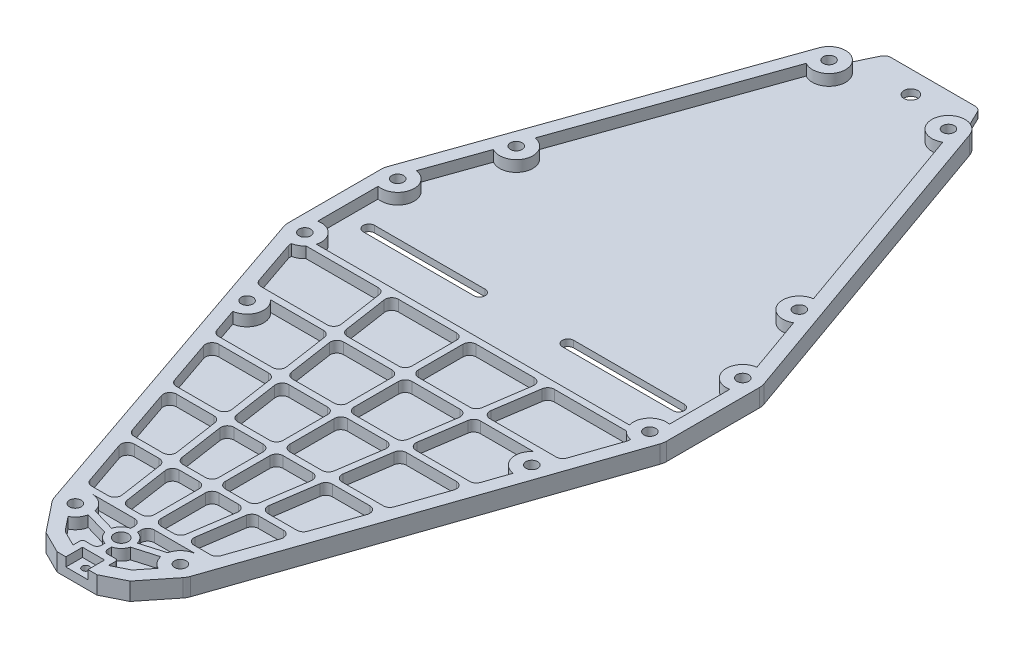
SolidWorks part; units mm, degrees
material "6061-T6 (SS)"
ref_plane "Front Plane" through (0, 0, 0) normal (0, 0, 1) x (1, 0, 0)
ref_plane "Top Plane" through (0, 0, 0) normal (0, 1, 0) x (1, 0, 0)
ref_plane "Right Plane" through (0, 0, 0) normal (1, 0, 0) x (0, 0, -1)
sketch "Sketch1" plane through (0, 0, 0) normal (0, 1, 0) x (1, 0, 0)
  line L0 (0, 0) -> (0, 185) construction
  line L1 (0, 0) -> (0, -202)
  line L2 (19.1123, 185) -> (-19.1123, 185)
  line L3 (-21.8169, 183.2982) -> (-27, 172.5)
  line L4 (-27, 165) -> (-78, 21) construction
  line L5 (-78, 21) -> (-78, -21) construction
  line L6 (-78, -21) -> (-23.75, -179) construction
  line L7 (-34.0697, 167.5039) -> (-85.5, 22.2889)
  line L8 (-85.5, 0) -> (-85.5, 22.2889)
  line L12 (-85.5, -21) -> (-85.5, 21)
  line L13 (-85.5, 0) -> (-85.5, -22.2517)
  line L14 (-30.8435, -181.4356) -> (-85.5, -22.2517)
  line L15 (9, -202) -> (-9, -202)
  line L16 (-9, -202) -> (-19, -197)
  line L17 (-19, -197) -> (-29.6428, -183.6395)
  line L18 (78, -21) -> (23.75, -179) construction
  line L19 (78, 21) -> (78, -21) construction
  line L20 (27, 165) -> (78, 21) construction
  line L21 (19, -197) -> (29.6428, -183.6395)
  line L22 (9, -202) -> (19, -197)
  line L23 (30.8435, -181.4356) -> (85.5, -22.2517)
  line L24 (85.5, 0) -> (85.5, -22.2517)
  line L25 (85.5, -21) -> (85.5, 21)
  line L29 (85.5, 0) -> (85.5, 22.2889)
  line L30 (34.0697, 167.5039) -> (85.5, 22.2889)
  line L31 (21.8169, 183.2982) -> (27, 172.5)
  line L32 (85.5, 0) -> (-85.5, 0) construction
  line L35 (-20, 0) -> (-70, 0) construction
  line L36 (-20, -2.55) -> (-70, -2.55)
  line L37 (-20, 2.55) -> (-70, 2.55)
  line L38 (20, 0) -> (70, 0) construction
  line L39 (20, -2.55) -> (70, -2.55)
  line L40 (20, 2.55) -> (70, 2.55)
  circle A0 centre (0, 0) radius 4.5
  circle A1 centre (0, 175) radius 3.15
  circle A2 centre (-27, 165) radius 2.65
  circle A3 centre (-78, 21) radius 2.65
  circle A4 centre (-78, -21) radius 2.65
  circle A5 centre (-23.75, -179) radius 2.65
  circle A6 centre (0, -198) radius 1.65
  circle A7 centre (0, -182) radius 3.15
  circle A9 centre (-27, 165) radius 7.5
  circle A10 centre (-78, 21) radius 7.5
  circle A11 centre (-78, -21) radius 7.5
  circle A12 centre (-23.75, -179) radius 7.5
  circle A13 centre (-63.9784, 60.5903) radius 2.65
  circle A14 centre (-63.9784, 60.5903) radius 7.5
  circle A15 centre (-64.3607, -60.7237) radius 2.65
  circle A16 centre (-64.3607, -60.7237) radius 7.5
  circle A17 centre (64.3607, -60.7237) radius 7.5
  circle A18 centre (64.3607, -60.7237) radius 2.65
  circle A19 centre (63.9784, 60.5903) radius 7.5
  circle A20 centre (63.9784, 60.5903) radius 2.65
  circle A21 centre (23.75, -179) radius 7.5
  circle A22 centre (78, -21) radius 7.5
  circle A23 centre (78, 21) radius 7.5
  circle A24 centre (27, 165) radius 7.5
  circle A25 centre (23.75, -179) radius 2.65
  circle A26 centre (78, -21) radius 2.65
  circle A27 centre (78, 21) radius 2.65
  circle A28 centre (27, 165) radius 2.65
  arc A31 (-20, -2.55) -> (-20, 2.55) centre (-20, 0) ccw
  arc A32 (-70, 2.55) -> (-70, -2.55) centre (-70, 0) ccw
  arc A33 (20, -2.55) -> (20, 2.55) centre (20, 0) cw
  arc A34 (70, 2.55) -> (70, -2.55) centre (70, 0) cw
  arc A35 (21.8169, 183.2982) -> (19.1123, 185) centre (19.1123, 182) ccw
  arc A36 (-19.1123, 185) -> (-21.8169, 183.2982) centre (-19.1123, 182) ccw
  point P73 (-45, 0)
  point P80 (45, 0)
  point P87 (21, 185)
  point P90 (-21, 185)
  dimension "D14" = 3.3
  dimension "D15" = 6.3
  dimension "D16" = 5.3
  dimension "D17" = 5.3
  dimension "D18" = 9
  dimension "D19" = 5.3
  dimension "D20" = 5.3
  dimension "D21" = 6.3
  dimension "D24" = 15
  dimension "D23" = 15
  dimension "D25" = 15
  dimension "D26" = 15
  dimension "D27" = 5.3
  dimension "D28" = 15
  dimension "D31" = 5.3
  dimension "D32" = 15
  dimension "D45" = 70
  dimension "D43" = 2.55
  dimension "D47" = 3
  dimension "D1" = 21
  dimension "D2" = 21
  dimension "D3" = 165
  dimension "D4" = 182
  dimension "79" = 179
  dimension "D5" = 175
  dimension "D6" = 198
  dimension "D7" = 185
  dimension "D8" = 202
  dimension "D9" = 27
  dimension "D10" = 78
  dimension "D11" = 78
  dimension "D12" = 23.75
  dimension "D13" = 0
  dimension "D22" = 21
  dimension "D29" = 42
  dimension "D30" = 42
  dimension "D33" = 7.5
  dimension "D34" = 7.5
  dimension "D35" = 7.5
  dimension "D36" = 22.2889
  dimension "D37" = 7.5
  dimension "D38" = 7.5
  dimension "D39" = 10
  dimension "D40" = 5
  dimension "D41" = 9
  dimension "D42" = 13.3605
  dimension "D44" = 50
  dimension "D46" = 7.5
extrude "Boss-Extrude2" add sketch "Sketch1" along normal blind 8
sketch "Sketch2" plane through (0, 8, 0) normal (0, 1, 0) x (1, 0, 0)
  line L0 (0, -202) -> (0, 185) construction
  line L1 (9, -202) -> (-9, -202) construction
  line L2 (19.1123, 185) -> (-19.1123, 185) construction
  line L3 (-30.8672, 158.5739) -> (-76.9607, 28.4276)
  line L4 (-34.0697, 167.5039) -> (-85.0697, 23.5039) construction
  line L5 (-79.5, 13.6515) -> (-79.5, -13.6515)
  line L6 (-85.5, -21) -> (-85.5, 21) construction
  line L7 (-29.6367, -166.4742) -> (-77.0323, -28.4373)
  line L8 (-30.8435, -181.4356) -> (-85.0935, -23.4356) construction
  line L9 (-20.3446, -185.6823) -> (-15.5447, -191.7078)
  line L10 (-14.5399, -192.5219) -> (-8.217, -195.6833)
  line L11 (-6.8754, -196) -> (6.8754, -196)
  line L12 (-19, -197) -> (-29.6428, -183.6395) construction
  line L13 (-9, -202) -> (-19, -197) construction
  line L14 (-8, -202) -> (-8, -192.5)
  line L15 (-7, -191.5) -> (-3.5, -191.5)
  line L16 (0, -168.5) -> (-28.9412, -168.5) construction
  line L17 (-1.5, -23) -> (-70.7716, -23)
  line L18 (-1.5, -29) -> (-1.5, -49.1)
  line L19 (-4.5, -52.1) -> (-27.6998, -52.1)
  line L20 (-30.6671, -49.5418) -> (-33.6601, -29.4418)
  line L21 (-30.6928, -26) -> (-4.5, -26)
  line L22 (-1.5, -58.1) -> (-1.5, -78.2)
  line L23 (-4.5, -81.2) -> (-23.3668, -81.2)
  line L24 (-26.3341, -78.6418) -> (-29.327, -58.5418)
  line L25 (-26.3597, -55.1) -> (-4.5, -55.1)
  line L26 (-1.5, -87.2) -> (-1.5, -107.3)
  line L27 (-4.5, -110.3) -> (-19.0338, -110.3)
  line L28 (-22.001, -107.7418) -> (-24.994, -87.6418)
  line L29 (-22.0267, -84.2) -> (-4.5, -84.2)
  line L30 (-1.5, -145.4) -> (-1.5, -165.5)
  line L31 (-4.5, -168.5) -> (-10.3677, -168.5)
  line L32 (-13.335, -165.9418) -> (-16.3279, -145.8418)
  line L33 (-13.3606, -142.4) -> (-4.5, -142.4)
  line L34 (-1.5, -116.3) -> (-1.5, -136.4)
  line L35 (-4.5, -139.4) -> (-14.7007, -139.4)
  line L36 (-17.668, -136.8418) -> (-20.6609, -116.7418)
  line L37 (-17.6936, -113.3) -> (-4.5, -113.3)
  line L42 (-16.25, -179) -> (-6, -182)
  line L43 (-23.75, -171.5) -> (-4.5, -171.5)
  line L44 (-14.4706, -168.5) -> (-36.1358, -23) construction
  line L45 (-1.5, -174.5) -> (-1.5, -176.1905)
  line L46 (-16.4051, -180.5175) -> (-5.7747, -183.6289)
  line L47 (-16.4258, -177.3856) -> (-5.8078, -180.4933)
  line L48 (-36.8247, -28.5582) -> (-33.8318, -48.6582)
  line L49 (-36.7991, -52.1) -> (-66.7658, -52.1)
  line L50 (-69.6032, -50.0742) -> (-76.5046, -29.9742)
  line L51 (-73.6672, -26) -> (-39.792, -26)
  line L53 (-32.466, -81.2) -> (-56.7742, -81.2)
  line L54 (-59.6116, -79.1742) -> (-67.8776, -55.1)
  line L55 (-67.8776, -55.1) -> (-35.459, -55.1)
  line L56 (-28.1586, -86.7582) -> (-25.1657, -106.8582)
  line L57 (-28.133, -110.3) -> (-46.7826, -110.3)
  line L58 (-49.62, -108.2742) -> (-56.5214, -88.1742)
  line L59 (-53.684, -84.2) -> (-31.1259, -84.2)
  line L62 (-39.6283, -137.3742) -> (-46.5298, -117.2742)
  line L63 (-43.6924, -113.3) -> (-26.7929, -113.3)
  line L65 (-19.4669, -168.5) -> (-26.7993, -168.5)
  line L66 (-28.9412, -168.5) -> (-36.5382, -146.3742)
  line L68 (-32.4917, -57.6582) -> (-29.4987, -77.7582)
  line L70 (-20.8327, -135.9582) -> (-23.8256, -115.8582)
  line L71 (-16.4996, -165.0582) -> (-19.4925, -144.9582)
  line L72 (-22.4598, -142.4) -> (-33.7008, -142.4)
  line L73 (-23.7999, -139.4) -> (-36.7909, -139.4)
  line L74 (-1.5, -189.5) -> (-1.5, -187.8095)
  line L75 (14.4706, -168.5) -> (36.1358, -23) construction
  line L76 (0, -168.5) -> (28.9412, -168.5) construction
  line L77 (1.5, -189.5) -> (1.5, -187.8095)
  line L78 (23.7999, -139.4) -> (36.7909, -139.4)
  line L79 (22.4598, -142.4) -> (33.7008, -142.4)
  line L80 (16.4996, -165.0582) -> (19.4925, -144.9582)
  line L81 (20.8327, -135.9582) -> (23.8256, -115.8582)
  line L82 (32.4917, -57.6582) -> (29.4987, -77.7582)
  line L83 (28.9412, -168.5) -> (36.5382, -146.3742)
  line L84 (19.4669, -168.5) -> (26.7993, -168.5)
  line L85 (43.6924, -113.3) -> (26.7929, -113.3)
  line L86 (39.6283, -137.3742) -> (46.5298, -117.2742)
  line L87 (53.684, -84.2) -> (31.1259, -84.2)
  line L88 (49.62, -108.2742) -> (56.5214, -88.1742)
  line L89 (28.133, -110.3) -> (46.7826, -110.3)
  line L90 (28.1586, -86.7582) -> (25.1657, -106.8582)
  line L91 (67.8776, -55.1) -> (35.459, -55.1)
  line L92 (59.6116, -79.1742) -> (67.8776, -55.1)
  line L93 (32.466, -81.2) -> (56.7742, -81.2)
  line L94 (73.6672, -26) -> (39.792, -26)
  line L95 (69.6032, -50.0742) -> (76.5046, -29.9742)
  line L96 (36.7991, -52.1) -> (66.7658, -52.1)
  line L97 (36.8247, -28.5582) -> (33.8318, -48.6582)
  line L98 (16.4258, -177.3856) -> (5.8078, -180.4933)
  line L99 (16.4051, -180.5175) -> (5.7747, -183.6289)
  line L100 (1.5, -174.5) -> (1.5, -176.1905)
  line L101 (23.75, -171.5) -> (4.5, -171.5)
  line L102 (16.25, -179) -> (6, -182)
  line L103 (17.6936, -113.3) -> (4.5, -113.3)
  line L104 (17.668, -136.8418) -> (20.6609, -116.7418)
  line L105 (4.5, -139.4) -> (14.7007, -139.4)
  line L106 (1.5, -116.3) -> (1.5, -136.4)
  line L107 (13.3606, -142.4) -> (4.5, -142.4)
  line L108 (13.335, -165.9418) -> (16.3279, -145.8418)
  line L109 (4.5, -168.5) -> (10.3677, -168.5)
  line L110 (1.5, -145.4) -> (1.5, -165.5)
  line L111 (22.0267, -84.2) -> (4.5, -84.2)
  line L112 (22.001, -107.7418) -> (24.994, -87.6418)
  line L113 (4.5, -110.3) -> (19.0338, -110.3)
  line L114 (1.5, -87.2) -> (1.5, -107.3)
  line L115 (26.3597, -55.1) -> (4.5, -55.1)
  line L116 (26.3341, -78.6418) -> (29.327, -58.5418)
  line L117 (4.5, -81.2) -> (23.3668, -81.2)
  line L118 (1.5, -58.1) -> (1.5, -78.2)
  line L119 (30.6928, -26) -> (4.5, -26)
  line L120 (30.6671, -49.5418) -> (33.6601, -29.4418)
  line L121 (4.5, -52.1) -> (27.6998, -52.1)
  line L122 (1.5, -29) -> (1.5, -49.1)
  line L123 (1.5, -23) -> (70.7716, -23)
  line L124 (7, -191.5) -> (3.5, -191.5)
  line L125 (8, -202) -> (8, -192.5)
  line L126 (14.5399, -192.5219) -> (8.217, -195.6833)
  line L127 (20.3446, -185.6823) -> (15.5447, -191.7078)
  line L128 (29.6367, -166.4742) -> (77.0323, -28.4373)
  line L129 (79.5, 13.6515) -> (79.5, -13.6515)
  line L130 (30.8672, 158.5739) -> (76.9607, 28.4276)
  line L131 (-27, 172.5) -> (-21, 185)
  line L132 (-21, 185) -> (21, 185)
  line L133 (21, 185) -> (27, 172.5)
  line L134 (-70.7716, -23) -> (-79.5, -13.6515)
  line L135 (70.7716, -23) -> (79.5, -13.6515)
  line L136 (79.5, 13.6515) -> (76.9607, 28.4276)
  line L137 (-79.5, 13.6515) -> (-76.9607, 28.4276)
  line L138 (-70.7716, -23) -> (70.7716, -23)
  circle A0 centre (-27, 165) radius 7.5
  circle A1 centre (-63.9784, 60.5903) radius 7.5
  circle A2 centre (-78, 21) radius 7.5
  circle A3 centre (-78, -21) radius 7.5
  circle A4 centre (-64.3607, -60.7237) radius 7.5
  circle A5 centre (-23.75, -179) radius 7.5
  arc A6 (-8.217, -195.6833) -> (-6.8754, -196) centre (-6.8754, -193) ccw
  arc A7 (-15.5447, -191.7078) -> (-14.5399, -192.5219) centre (-13.1982, -189.8386) ccw
  circle A8 centre (0, -182) radius 6
  arc A9 (-29.6367, -166.4742) -> (-26.7993, -168.5) centre (-26.7993, -165.5) ccw
  arc A10 (-19.4925, -144.9582) -> (-22.4598, -142.4) centre (-22.4598, -145.4) ccw
  arc A11 (-36.5382, -146.3742) -> (-33.7008, -142.4) centre (-33.7008, -145.4) cw
  arc A12 (-16.3279, -145.8418) -> (-13.3606, -142.4) centre (-13.3606, -145.4) cw
  arc A13 (-1.5, -145.4) -> (-4.5, -142.4) centre (-4.5, -145.4) ccw
  arc A14 (-1.5, -165.5) -> (-4.5, -168.5) centre (-4.5, -165.5) cw
  arc A15 (-10.3677, -168.5) -> (-13.335, -165.9418) centre (-10.3677, -165.5) cw
  arc A16 (-16.4996, -165.0582) -> (-19.4669, -168.5) centre (-19.4669, -165.5) cw
  arc A17 (-4.5, -171.5) -> (-1.5, -174.5) centre (-4.5, -174.5) cw
  arc A18 (-56.5214, -88.1742) -> (-53.684, -84.2) centre (-53.684, -87.2) cw
  arc A19 (-28.1586, -86.7582) -> (-31.1259, -84.2) centre (-31.1259, -87.2) ccw
  arc A20 (-29.4987, -77.7582) -> (-32.466, -81.2) centre (-32.466, -78.2) cw
  arc A21 (-24.994, -87.6418) -> (-22.0267, -84.2) centre (-22.0267, -87.2) cw
  arc A22 (-23.3668, -81.2) -> (-26.3341, -78.6418) centre (-23.3668, -78.2) cw
  arc A23 (-1.5, -78.2) -> (-4.5, -81.2) centre (-4.5, -78.2) cw
  arc A24 (-1.5, -87.2) -> (-4.5, -84.2) centre (-4.5, -87.2) ccw
  arc A25 (-1.5, -107.3) -> (-4.5, -110.3) centre (-4.5, -107.3) cw
  arc A26 (-19.0338, -110.3) -> (-22.001, -107.7418) centre (-19.0338, -107.3) cw
  arc A27 (-46.7826, -110.3) -> (-49.62, -108.2742) centre (-46.7826, -107.3) cw
  arc A28 (-25.1657, -106.8582) -> (-28.133, -110.3) centre (-28.133, -107.3) cw
  arc A29 (-23.8256, -115.8582) -> (-26.7929, -113.3) centre (-26.7929, -116.3) ccw
  arc A30 (-46.5298, -117.2742) -> (-43.6924, -113.3) centre (-43.6924, -116.3) cw
  arc A31 (-36.7909, -139.4) -> (-39.6283, -137.3742) centre (-36.7909, -136.4) cw
  arc A32 (-23.7999, -139.4) -> (-20.8327, -135.9582) centre (-23.7999, -136.4) ccw
  arc A33 (-14.7007, -139.4) -> (-17.668, -136.8418) centre (-14.7007, -136.4) cw
  arc A34 (-1.5, -136.4) -> (-4.5, -139.4) centre (-4.5, -136.4) cw
  arc A35 (-1.5, -116.3) -> (-4.5, -113.3) centre (-4.5, -116.3) ccw
  arc A36 (-20.6609, -116.7418) -> (-17.6936, -113.3) centre (-17.6936, -116.3) cw
  arc A37 (-56.7742, -81.2) -> (-59.6116, -79.1742) centre (-56.7742, -78.2) cw
  arc A38 (-76.5046, -29.9742) -> (-73.6672, -26) centre (-73.6672, -29) cw
  arc A39 (-66.7658, -52.1) -> (-69.6032, -50.0742) centre (-66.7658, -49.1) cw
  arc A40 (-33.8318, -48.6582) -> (-36.7991, -52.1) centre (-36.7991, -49.1) cw
  arc A41 (-36.8247, -28.5582) -> (-39.792, -26) centre (-39.792, -29) ccw
  arc A42 (-33.6601, -29.4418) -> (-30.6928, -26) centre (-30.6928, -29) cw
  arc A43 (-27.6998, -52.1) -> (-30.6671, -49.5418) centre (-27.6998, -49.1) cw
  arc A44 (-29.327, -58.5418) -> (-26.3597, -55.1) centre (-26.3597, -58.1) cw
  arc A45 (-1.5, -58.1) -> (-4.5, -55.1) centre (-4.5, -58.1) ccw
  arc A46 (-1.5, -49.1) -> (-4.5, -52.1) centre (-4.5, -49.1) cw
  arc A47 (-1.5, -29) -> (-4.5, -26) centre (-4.5, -29) ccw
  arc A48 (-1.5, -189.5) -> (-3.5, -191.5) centre (-3.5, -189.5) cw
  arc A49 (-8, -192.5) -> (-7, -191.5) centre (-7, -192.5) cw
  arc A50 (8, -192.5) -> (7, -191.5) centre (7, -192.5) ccw
  arc A51 (1.5, -189.5) -> (3.5, -191.5) centre (3.5, -189.5) ccw
  arc A52 (1.5, -29) -> (4.5, -26) centre (4.5, -29) cw
  arc A53 (1.5, -49.1) -> (4.5, -52.1) centre (4.5, -49.1) ccw
  arc A54 (1.5, -58.1) -> (4.5, -55.1) centre (4.5, -58.1) cw
  arc A55 (29.327, -58.5418) -> (26.3597, -55.1) centre (26.3597, -58.1) ccw
  arc A56 (27.6998, -52.1) -> (30.6671, -49.5418) centre (27.6998, -49.1) ccw
  arc A57 (33.6601, -29.4418) -> (30.6928, -26) centre (30.6928, -29) ccw
  arc A58 (36.8247, -28.5582) -> (39.792, -26) centre (39.792, -29) cw
  arc A59 (33.8318, -48.6582) -> (36.7991, -52.1) centre (36.7991, -49.1) ccw
  arc A60 (66.7658, -52.1) -> (69.6032, -50.0742) centre (66.7658, -49.1) ccw
  arc A61 (76.5046, -29.9742) -> (73.6672, -26) centre (73.6672, -29) ccw
  arc A62 (56.7742, -81.2) -> (59.6116, -79.1742) centre (56.7742, -78.2) ccw
  arc A63 (20.6609, -116.7418) -> (17.6936, -113.3) centre (17.6936, -116.3) ccw
  arc A64 (1.5, -116.3) -> (4.5, -113.3) centre (4.5, -116.3) cw
  arc A65 (1.5, -136.4) -> (4.5, -139.4) centre (4.5, -136.4) ccw
  arc A66 (14.7007, -139.4) -> (17.668, -136.8418) centre (14.7007, -136.4) ccw
  arc A67 (23.7999, -139.4) -> (20.8327, -135.9582) centre (23.7999, -136.4) cw
  arc A68 (36.7909, -139.4) -> (39.6283, -137.3742) centre (36.7909, -136.4) ccw
  arc A69 (46.5298, -117.2742) -> (43.6924, -113.3) centre (43.6924, -116.3) ccw
  arc A70 (23.8256, -115.8582) -> (26.7929, -113.3) centre (26.7929, -116.3) cw
  arc A71 (25.1657, -106.8582) -> (28.133, -110.3) centre (28.133, -107.3) ccw
  arc A72 (46.7826, -110.3) -> (49.62, -108.2742) centre (46.7826, -107.3) ccw
  arc A73 (19.0338, -110.3) -> (22.001, -107.7418) centre (19.0338, -107.3) ccw
  arc A74 (1.5, -107.3) -> (4.5, -110.3) centre (4.5, -107.3) ccw
  arc A75 (1.5, -87.2) -> (4.5, -84.2) centre (4.5, -87.2) cw
  arc A76 (1.5, -78.2) -> (4.5, -81.2) centre (4.5, -78.2) ccw
  arc A77 (23.3668, -81.2) -> (26.3341, -78.6418) centre (23.3668, -78.2) ccw
  arc A78 (24.994, -87.6418) -> (22.0267, -84.2) centre (22.0267, -87.2) ccw
  arc A79 (29.4987, -77.7582) -> (32.466, -81.2) centre (32.466, -78.2) ccw
  arc A80 (28.1586, -86.7582) -> (31.1259, -84.2) centre (31.1259, -87.2) cw
  arc A81 (56.5214, -88.1742) -> (53.684, -84.2) centre (53.684, -87.2) ccw
  arc A82 (4.5, -171.5) -> (1.5, -174.5) centre (4.5, -174.5) ccw
  arc A83 (16.4996, -165.0582) -> (19.4669, -168.5) centre (19.4669, -165.5) ccw
  arc A84 (10.3677, -168.5) -> (13.335, -165.9418) centre (10.3677, -165.5) ccw
  arc A85 (1.5, -165.5) -> (4.5, -168.5) centre (4.5, -165.5) ccw
  arc A86 (1.5, -145.4) -> (4.5, -142.4) centre (4.5, -145.4) cw
  arc A87 (16.3279, -145.8418) -> (13.3606, -142.4) centre (13.3606, -145.4) ccw
  arc A88 (36.5382, -146.3742) -> (33.7008, -142.4) centre (33.7008, -145.4) ccw
  arc A89 (19.4925, -144.9582) -> (22.4598, -142.4) centre (22.4598, -145.4) cw
  arc A90 (29.6367, -166.4742) -> (26.7993, -168.5) centre (26.7993, -165.5) cw
  arc A91 (15.5447, -191.7078) -> (14.5399, -192.5219) centre (13.1982, -189.8386) cw
  arc A92 (8.217, -195.6833) -> (6.8754, -196) centre (6.8754, -193) cw
  circle A93 centre (23.75, -179) radius 7.5
  circle A94 centre (64.3607, -60.7237) radius 7.5
  circle A95 centre (78, -21) radius 7.5
  circle A96 centre (78, 21) radius 7.5
  circle A97 centre (63.9784, 60.5903) radius 7.5
  circle A98 centre (27, 165) radius 7.5
  arc A99 (-32.4917, -57.6582) -> (-35.459, -55.1) centre (-35.459, -58.1) ccw
  arc A100 (32.4917, -57.6582) -> (35.459, -55.1) centre (35.459, -58.1) cw
  point P51 (-7.5836, -196)
  point P54 (-15.1322, -192.2257)
  point P85 (-13.2633, -84.2)
  point P120 (-19.8735, -142.4)
  point P123 (-37.9027, -142.4)
  point P126 (-16.8404, -142.4)
  point P129 (-1.5, -142.4)
  point P132 (-1.5, -168.5)
  point P135 (-12.9541, -168.5)
  point P138 (-15.9871, -168.5)
  point P144 (-28.5395, -84.2)
  point P147 (-28.9862, -81.2)
  point P150 (-25.5065, -84.2)
  point P155 (-1.5, -81.2)
  point P158 (-1.5, -84.2)
  point P161 (-1.5, -110.3)
  point P166 (-48.9244, -110.3)
  point P169 (-24.6532, -110.3)
  point P172 (-24.2065, -113.3)
  point P175 (-47.8943, -113.3)
  point P178 (-38.9328, -139.4)
  point P181 (-20.3202, -139.4)
  point P186 (-1.5, -139.4)
  point P189 (-1.5, -113.3)
  point P192 (-21.1734, -113.3)
  point P195 (-58.916, -81.2)
  point P198 (-77.8692, -26)
  point P205 (-37.2056, -26)
  point P208 (-34.1725, -26)
  point P213 (-29.8395, -55.1)
  point P216 (-1.5, -55.1)
  point P219 (-1.5, -52.1)
  point P222 (-1.5, -26)
  point P228 (-1.5, -191.5)
  point P231 (-8, -191.5)
  point P390 (0, -196)
  point P396 (8, -191.5)
  point P397 (1.5, -191.5)
  point P398 (1.5, -26)
  point P399 (1.5, -52.1)
  point P400 (1.5, -55.1)
  point P401 (29.8395, -55.1)
  point P402 (34.1725, -26)
  point P403 (37.2056, -26)
  point P404 (77.8692, -26)
  point P405 (58.916, -81.2)
  point P406 (21.1734, -113.3)
  point P407 (1.5, -113.3)
  point P408 (1.5, -139.4)
  point P409 (20.3202, -139.4)
  point P410 (38.9328, -139.4)
  point P411 (47.8943, -113.3)
  point P412 (24.2065, -113.3)
  point P413 (24.6532, -110.3)
  point P414 (48.9244, -110.3)
  point P415 (1.5, -110.3)
  point P416 (1.5, -84.2)
  point P417 (1.5, -81.2)
  point P418 (25.5065, -84.2)
  point P419 (28.9862, -81.2)
  point P420 (28.5395, -84.2)
  point P421 (15.9871, -168.5)
  point P422 (12.9541, -168.5)
  point P423 (1.5, -168.5)
  point P424 (1.5, -142.4)
  point P425 (16.8404, -142.4)
  point P426 (37.9027, -142.4)
  point P427 (19.8735, -142.4)
  point P428 (15.1322, -192.2257)
  point P429 (7.5836, -196)
  point P434 (-32.8726, -55.1)
  point P437 (32.8726, -55.1)
  dimension "D1" = 15
  dimension "D2" = 15
  dimension "D13" = 3
  dimension "D16" = 12
  dimension "D66" = 3
  dimension "D72" = 3
  dimension "D73" = 3
  dimension "D74" = 2
  dimension "D75" = 1
  dimension "D78" = 3
  dimension "D3" = 6
  dimension "D4" = 6
  dimension "D5" = 6
  dimension "D6" = 6
  dimension "D8" = 6
  dimension "D9" = 6
  dimension "D10" = 6
  dimension "D11" = 6
  dimension "D12" = 6
  dimension "D14" = 10.5
  dimension "D15" = 6.5
  dimension "D17" = 2
  dimension "D18" = 3
  dimension "D19" = 26.1
  dimension "D20" = 26.1
  dimension "D21" = 3
  dimension "D22" = 3
  dimension "D23" = 3
  dimension "D24" = 147.1042
  dimension "D25" = 360
  dimension "D26" = 1.5
  dimension "D27" = 1.5
  dimension "D28" = 3
  dimension "D29" = 26.1
  dimension "D30" = 1.5
  dimension "D31" = 26.1
  dimension "D32" = 1.5
  dimension "D33" = 3
  dimension "D34" = 3
  dimension "D35" = 1.5
  dimension "D36" = 26.1
  dimension "D37" = 3
  dimension "D38" = 1.5
  dimension "D39" = 1.5
  dimension "D40" = 1.5
  dimension "D41" = 1.5
  dimension "D42" = 3
  dimension "D43" = 0
  dimension "D44" = 0
  dimension "D45" = 360
  dimension "D46" = 1.5
  dimension "D47" = 0
  dimension "D48" = 3
  dimension "D49" = 1.5
  dimension "D50" = 1.5
  dimension "D51" = 0
  dimension "D52" = 0
  dimension "D53" = 360
  dimension "D54" = 3
  dimension "D55" = 3
  dimension "D56" = 3
  dimension "D57" = 0
  dimension "D58" = 0
  dimension "D59" = 3
  dimension "D60" = 3
  dimension "D61" = 0
  dimension "D62" = 0
  dimension "D63" = 0
  dimension "D64" = 3
  dimension "D65" = 3
  dimension "D67" = 0
  dimension "D68" = 3
  dimension "D69" = 3
  dimension "D70" = 0
  dimension "D71" = 5.1912
  dimension "D76" = 42
  dimension "D77" = 13.8654
extrude "Cut-Extrude1" cut sketch "Sketch2" against normal blind 5
sketch "Sketch3" plane through (0, 8, 0) normal (0, 1, 0) x (1, 0, 0)
  line L0 (-5, -202) -> (-5, -194.5)
  line L1 (9, -202) -> (-9, -202) construction
  line L2 (-5, -194.5) -> (5, -194.5)
  line L3 (5, -194.5) -> (5, -202)
  line L4 (5, -202) -> (-5, -202)
  circle A0 centre (0, -198) radius 1.65 construction
  dimension "D1" = 10
  dimension "D2" = 5
  dimension "D3" = 7.5
extrude "Cut-Extrude2" cut sketch "Sketch3" against normal blind 4
equation "\"weightkg\"= \"SW-Mass\" / 1000"
